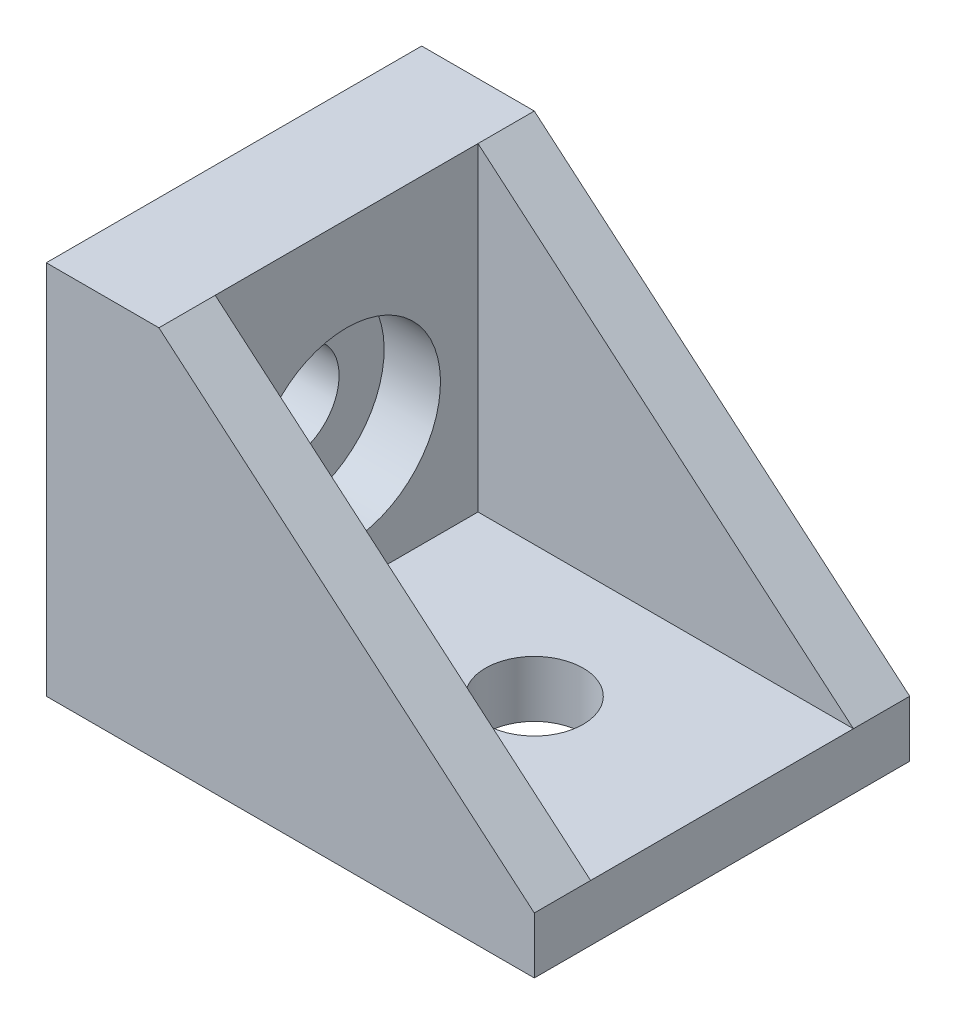
SolidWorks part; units mm, degrees
ref_plane "前视基准面" through (0, 0, 0) normal (0, 0, 1) x (1, 0, 0)
ref_plane "上视基准面" through (0, 0, 0) normal (0, 1, 0) x (1, 0, 0)
ref_plane "右视基准面" through (0, 0, 0) normal (1, 0, 0) x (0, 0, -1)
other "Configuration Table"
sketch "草图1" plane through (0, 0, 0) normal (0, 1, 0) x (1, 0, 0)
  line L1 (0, 0) -> (40, 0)
  line L2 (0, 0) -> (0, 20)
  line L3 (0, 20) -> (40, 20)
  line L4 (40, 0) -> (40, 20)
extrude "凸台-拉伸1" add sketch "草图1" along normal blind 20
sketch "草图2" plane through (0, 0, 0) normal (0, 0, 1) x (1, 0, 0)
  line L0 (0, 20) -> (6, 20)
  line L1 (0, 20) -> (40, 20) construction
  line L2 (6, 20) -> (6, 6)
  line L3 (6, 6) -> (40, 6)
  line L4 (40, 20) -> (40, 0) construction
  line L5 (6, 20) -> (40, 20)
  line L6 (40, 20) -> (40, 6)
  line M7 (40, 0) -> (40, 20)
  line M8 (40, 20) -> (0, 20)
extrude "切除-拉伸1" cut sketch "草图2" against normal blind 20 contours L2 L3 M7 M8
sketch "草图4" plane through (0, 0, 0) normal (-1, 0, 0) x (0, 0, 1)
  line L0 (-20, 20) -> (0, 0)
  circle A0 centre (-10, 10) radius 2.6
extrude "切除-拉伸2" cut sketch "草图4" against normal blind 20 contours L0 A0 | L0 A0
sketch "草图5" plane through (6, 0, 0) normal (1, 0, 0) x (0, 0, -1)
  circle A0 centre (10, 10) radius 5
extrude "切除-拉伸3" cut sketch "草图5" against normal blind 3
sketch "草图6" plane through (0, 6, 0) normal (0, 1, 0) x (1, 0, 0)
  line L1 (6, 20) -> (40, 20)
  line L2 (6, 20) -> (6, 0)
  line L3 (6, 0) -> (40, 0)
  line L4 (40, 20) -> (40, 0)
extrude "切除-拉伸4" cut sketch "草图6" against normal blind 3
sketch "草图7" plane through (0, 3, 0) normal (0, 1, 0) x (1, 0, 0)
  line L0 (6, 0) -> (40, 0) construction
  line L1 (6, 20) -> (26, 20)
  line L2 (6, 20) -> (6, 0)
  line L3 (6, 0) -> (26, 0)
  line L4 (26, 20) -> (26, 0)
  line L5 (6, 20) -> (26, 0)
  line L7 (26, 20) -> (40, 20)
  line L8 (26, 20) -> (26, 0)
  line L9 (26, 0) -> (40, 0)
  line L10 (40, 20) -> (40, 0)
  circle A0 centre (16, 10) radius 2.6
  line M7 (6, 0) -> (40, 0)
  line M8 (40, 0) -> (40, 20)
  line M9 (40, 20) -> (6, 20)
extrude "切除-拉伸5" cut sketch "草图7" against normal blind 3 contours L4 M9 M7 M8 | L5 A0 | L5 A0
sketch "草图9" plane through (0, 0, 0) normal (0, 0, 1) x (1, 0, 0)
  line L0 (6, 20) -> (26, 3)
  line L1 (26, 3) -> (6, 3)
  line L2 (6, 3) -> (6, 20)
extrude "凸台-拉伸2" add sketch "草图9" against normal blind 3
sketch "草图10" plane through (0, 0, -20) normal (0, 0, -1) x (-1, 0, 0)
  line L0 (-26, 3) -> (-6, 3)
  line L1 (-6, 3) -> (-6, 20)
  line L2 (-6, 20) -> (-26, 3)
extrude "凸台-拉伸3" add sketch "草图10" against normal blind 3
